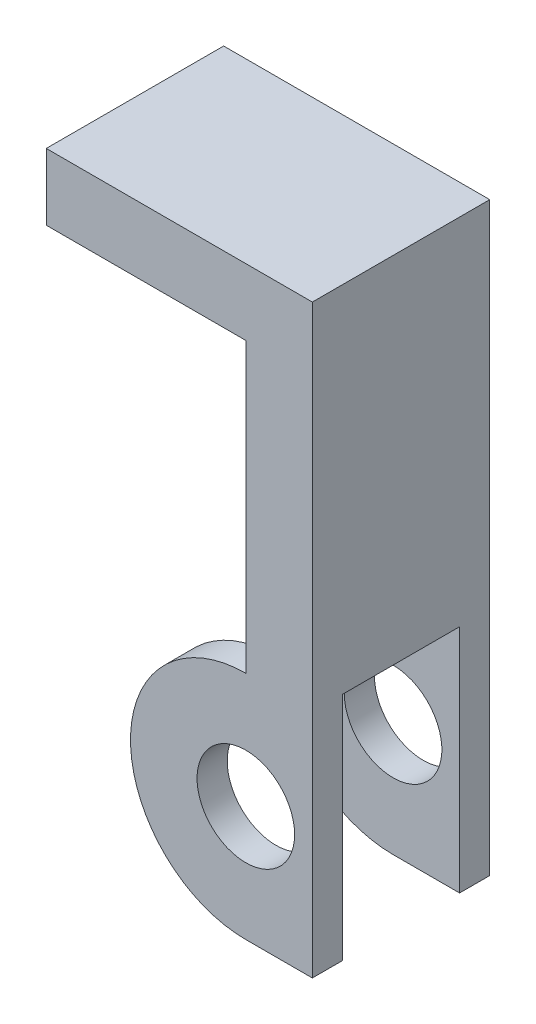
SolidWorks part; units mm, degrees
ref_plane "Front" through (0, 0, 0) normal (0, 0, 1) x (1, 0, 0)
ref_plane "Top" through (0, 0, 0) normal (0, 1, 0) x (1, 0, 0)
ref_plane "Right" through (0, 0, 0) normal (1, 0, 0) x (0, 0, -1)
sketch "Sketch1" plane through (0, 0, 0) normal (0, 0, 1) x (1, 0, 0)
  line L0 (0, 0) -> (0, 25.4)
  line L1 (0, 25.4) -> (-19.05, 25.4)
  line L2 (-19.05, 25.4) -> (-19.05, 20.6375)
  line L3 (-19.05, 20.6375) -> (-4.7625, 20.6375)
  line L4 (-4.7625, 20.6375) -> (-4.7625, 0)
  line L5 (0, 0) -> (0, -16.51)
  line L6 (0, -16.51) -> (-4.7625, -16.51)
  arc A0 (-4.7625, 0) -> (-4.7625, -16.51) centre (-4.7625, -8.255) ccw
  circle A1 centre (-4.7625, -8.255) radius 3.4925
  point P10 (0, 0)
  point P12 (-6.7822, -7.6248)
  point P13 (0, 0)
  dimension "D1" = 6.985
  dimension "D3" = 4.7625
  dimension "D2" = 4.7625
  dimension "D4" = 25.4
  dimension "D5" = 19.05
extrude "Boss-Extrude1" add sketch "Sketch1" along normal blind 12.7
sketch "Sketch2" plane through (0, -16.51, 0) normal (0, -1, 0) x (1, 0, 0)
  line L0 (0, 12.7) -> (0, 0) construction
  line L1 (0, 10.541) -> (-25.4, 10.541)
  line L2 (0, 10.541) -> (0, 2.159)
  line L3 (0, 2.159) -> (-25.4, 2.159)
  line L4 (-25.4, 10.541) -> (-25.4, 2.159)
  point P6 (0, 6.35)
  dimension "D1" = 8.382
  dimension "D2" = 25.4
extrude "Cut-Extrude1" cut sketch "Sketch2" against normal up to vertex (16.51 mm away) up to point (-4.7625, 0, 12.7)
